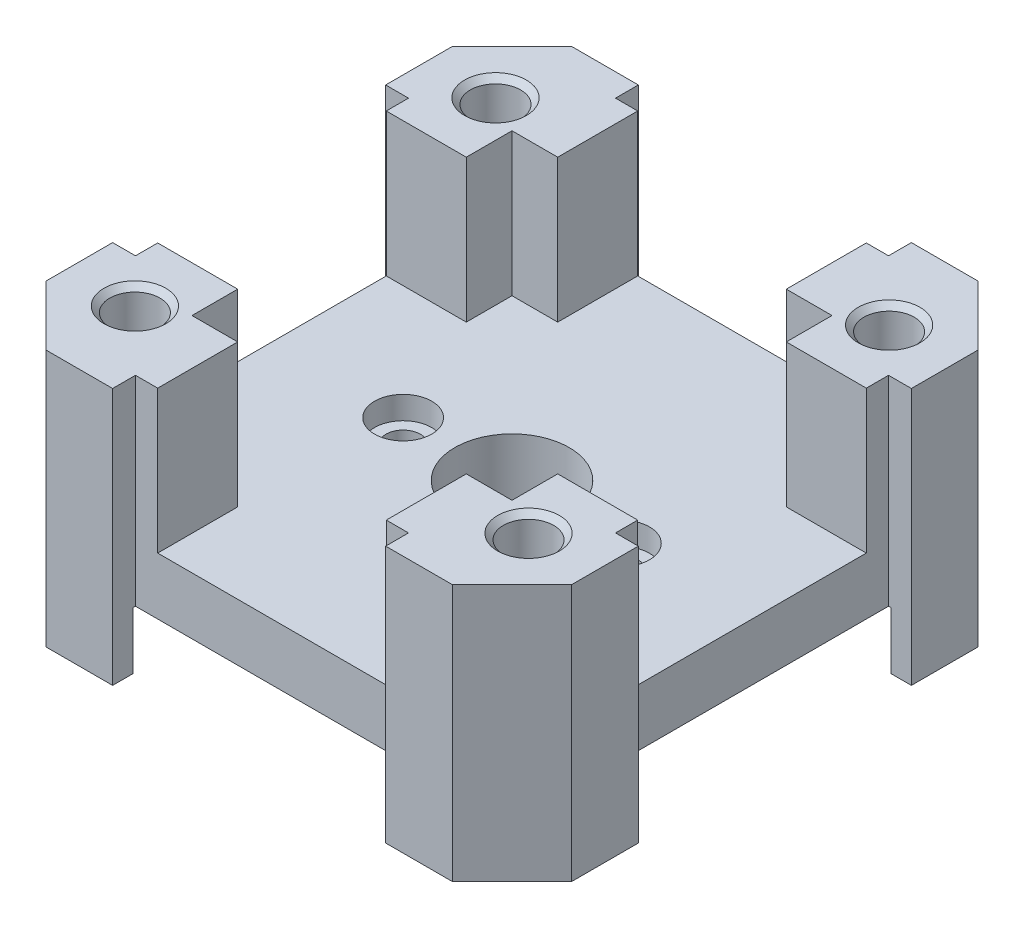
SolidWorks part; units mm, degrees
ref_plane "Front Plane" through (0, 0, 0) normal (0, 0, 1) x (1, 0, 0)
ref_plane "Top Plane" through (0, 0, 0) normal (0, 1, 0) x (1, 0, 0)
ref_plane "Right Plane" through (0, 0, 0) normal (1, 0, 0) x (0, 0, -1)
sketch "Sketch1" plane through (0, 0, 0) normal (0, 1, 0) x (1, 0, 0)
  line L0 (21, 42) -> (21, 0) construction
  line L5 (4.055, 0) -> (37.945, 0)
  line L6 (0, 4.055) -> (0, 37.945)
  line L7 (4.055, 42) -> (37.945, 42)
  line L8 (42, 4.055) -> (42, 37.945)
  line L9 (42, 21) -> (0, 21) construction
  line L10 (0, 37.945) -> (4.055, 42)
  line L11 (37.945, 42) -> (42, 37.945)
  line L12 (37.945, 0) -> (42, 4.055)
  line L13 (4.055, 0) -> (0, 4.055)
  circle A2 centre (11.475, 21) radius 1.5
  circle A3 centre (30.525, 21) radius 1.5
  circle A4 centre (21, 21) radius 5
  point P0 (0, 0)
  point P1 (0, 0)
  point P2 (42, 42)
  point P3 (0, 42)
  point P4 (42, 0)
  dimension "D4" = 3
  dimension "D5" = 3
  dimension "D13" = 10
  dimension "D1" = 42
  dimension "D2" = 42
  dimension "D3" = 19.05
  dimension "D10" = 33.89
  dimension "D9" = 33.89
  dimension "D14" = 16.945
  dimension "D6" = 21
  dimension "D7" = 21
  dimension "D8" = 9.525
  dimension "D11" = 33.89
  dimension "D12" = 33.89
  dimension "D15" = 16.945
  dimension "D16" = 16.945
  dimension "D17" = 16.945
extrude "Boss-Extrude1" add sketch "Sketch1" along normal blind 5
sketch "Sketch2" plane through (0, 5, 0) normal (0, 1, 0) x (1, 0, 0)
  line L45 (35, 7) -> (35, 35)
  line L47 (7, 7) -> (35, 7)
  line L49 (7, 35) -> (7, 7)
  line L51 (35, 35) -> (7, 35)
  line L53 (35, 7) -> (35, 35)
  line L55 (7, 7) -> (35, 7)
  line L57 (7, 35) -> (7, 7)
  line L59 (35, 35) -> (7, 35)
  dimension "D1" = 7
extrude "Boss-Extrude2" add sketch "Sketch2" along normal blind 12.5
sketch "Sketch3" plane through (0, 17.5, 0) normal (0, 1, 0) x (1, 0, 0)
  line L0 (4.055, 42) -> (0, 37.945) construction
  line L1 (0, 4.055) -> (4.055, 0) construction
  line L2 (35, 35) -> (7, 35) construction
  line L3 (7, 7) -> (35, 7) construction
  line L4 (7, 35) -> (7, 7) construction
  line L7 (21, 42) -> (21, 0) construction
  line L8 (37.945, 42) -> (4.055, 42) construction
  line L9 (4.055, 0) -> (37.945, 0) construction
  circle A0 centre (3.7797, 36.775) radius 2.2
  circle A7 centre (3.7797, 5.225) radius 2.2
  circle A8 centre (38.2203, 5.225) radius 2.2
  circle A9 centre (38.2203, 36.775) radius 2.2
  dimension "D1" = 4.4
  dimension "D2" = 3.5
  dimension "D3" = 1.775
  dimension "D4" = 3.2203
  dimension "D5" = 4.4
  dimension "D7" = 1.775
  dimension "D6" = 3.5
extrude "Cut-Extrude1" cut sketch "Sketch3" against normal blind 6
sketch "Sketch4" plane through (0, 0, 0) normal (-1, 0, 0) x (0, 0, 1)
  line L0 (-42, 17.5) -> (-42, 0) construction
  line L1 (-31, 28.0785) -> (-11, 28.0785)
  line L2 (-31, 28.0785) -> (-31, 5)
  line L3 (-31, 5) -> (-11, 5)
  line L4 (-11, 28.0785) -> (-11, 5)
  line L5 (-37.945, 0) -> (-4.055, 0) construction
  dimension "D1" = 20
  dimension "D2" = 11
  dimension "D3" = 5
extrude "Cut-Extrude2" cut sketch "Sketch4" against normal through all both and the other way through all
sketch "Sketch5" plane through (0, 0, -42) normal (0, 0, -1) x (-1, 0, 0)
  line L0 (-42, 17.5) -> (-42, 0) construction
  line L1 (-31, 18.3664) -> (-11, 18.3664)
  line L2 (-31, 18.3664) -> (-31, 5)
  line L3 (-31, 5) -> (-11, 5)
  line L4 (-11, 18.3664) -> (-11, 5)
  line L5 (-37.945, 0) -> (-4.055, 0) construction
  dimension "D1" = 20
  dimension "D2" = 11
  dimension "D3" = 5
extrude "Cut-Extrude3" cut sketch "Sketch5" against normal through all both and the other way through all
sketch "Sketch7" plane through (0, 0, 0) normal (0, -1, 0) x (1, 0, 0)
  line L0 (37.945, 0) -> (32.945, 0)
  line L1 (4.055, 0) -> (0, -4.055)
  line L2 (0, -4.055) -> (0, -9.055)
  line L3 (0, -37.945) -> (4.055, -42)
  line L4 (4.055, -42) -> (9.055, -42)
  line L5 (37.945, -42) -> (42, -37.945)
  line L6 (42, -37.945) -> (42, -32.945)
  line L7 (42, -4.055) -> (37.945, 0)
  line L8 (9.055, 2) -> (9.055, 0)
  line L9 (9.055, -42) -> (9.055, -44)
  line L10 (32.945, -44) -> (32.945, -42)
  line L11 (32.945, 0) -> (32.945, 2)
  line L12 (44, -9.055) -> (42, -9.055)
  line L13 (0, -9.055) -> (-2, -9.055)
  line L14 (-2, -32.945) -> (0, -32.945)
  line L15 (42, -32.945) -> (44, -32.945)
  line L16 (-2, -32.945) -> (-2, -38.7734)
  line L17 (-2, -3.2266) -> (-2, -38.7734) construction
  line L18 (9.055, 2) -> (3.2266, 2)
  line L19 (38.7734, 2) -> (3.2266, 2) construction
  line L20 (9.055, 0) -> (4.055, 0)
  line L21 (37.945, 0) -> (4.055, 0) construction
  line L22 (42, -9.055) -> (42, -4.055)
  line L23 (42, -37.945) -> (42, -4.055) construction
  line L24 (44, -9.055) -> (44, -3.2266)
  line L25 (44, -38.7734) -> (44, -3.2266) construction
  line L26 (32.945, -42) -> (37.945, -42)
  line L27 (4.055, -42) -> (37.945, -42) construction
  line L28 (32.945, -44) -> (38.7734, -44)
  line L29 (3.2266, -44) -> (38.7734, -44) construction
  line L31 (0, -32.945) -> (0, -37.945)
  line L32 (0, -4.055) -> (0, -37.945) construction
  line L44 (44, -3.2266) -> (38.7734, 2)
  line L45 (44, -38.7734) -> (44, -3.2266)
  line L46 (38.7734, -44) -> (44, -38.7734)
  line L47 (3.2266, -44) -> (38.7734, -44)
  line L48 (-2, -38.7734) -> (3.2266, -44)
  line L49 (-2, -3.2266) -> (-2, -38.7734)
  line L50 (3.2266, 2) -> (-2, -3.2266)
  line L51 (38.7734, 2) -> (3.2266, 2)
  line L52 (44, -3.2266) -> (38.7734, 2)
  line L53 (44, -38.7734) -> (44, -32.945)
  line L54 (38.7734, -44) -> (44, -38.7734)
  line L55 (3.2266, -44) -> (9.055, -44)
  line L56 (-2, -38.7734) -> (3.2266, -44)
  line L57 (-2, -3.2266) -> (-2, -9.055)
  line L58 (3.2266, 2) -> (-2, -3.2266)
  line L59 (38.7734, 2) -> (32.945, 2)
  dimension "D3" = 5
  dimension "D4" = 5
  dimension "D5" = 5
  dimension "D6" = 5
  dimension "D7" = 5
  dimension "D1" = 2
  dimension "D2" = 2
extrude "Boss-Extrude3" add sketch "Sketch7" along normal blind 5 and the other way up to surface
sketch "Sketch8" plane through (0, 5, 0) normal (0, 1, 0) x (1, 0, 0)
  circle A0 centre (11.475, 21) radius 2.5
  circle A1 centre (30.525, 21) radius 2.5
  dimension "D1" = 5
  dimension "D2" = 5
extrude "Cut-Extrude4" cut sketch "Sketch8" against normal blind 2
sketch "Sketch9" plane through (0, -5, 0) normal (0, -1, 0) x (1, 0, 0)
  line L0 (-0.2, -9.055) -> (-0.2, -3.9722)
  line L1 (-2, -9.055) -> (0, -9.055) construction
  line L2 (-0.2, -3.9722) -> (3.9722, 0.2)
  line L3 (3.9722, 0.2) -> (38.0278, 0.2)
  line L4 (38.0278, 0.2) -> (42.2, -3.9722)
  line L5 (42.2, -3.9722) -> (42.2, -38.0278)
  line L6 (42.2, -38.0278) -> (38.0278, -42.2)
  line L7 (38.0278, -42.2) -> (3.9722, -42.2)
  line L8 (3.9722, -42.2) -> (-0.2, -38.0278)
  line L9 (-0.2, -38.0278) -> (-0.2, -9.055)
  line L10 (0, -4.055) -> (4.055, 0) construction
  line L11 (4.055, 0) -> (9.055, 0) construction
  line L12 (0, -9.055) -> (0, -4.055) construction
  line L13 (37.945, 0) -> (42, -4.055) construction
  line L14 (42, -9.055) -> (42, -32.945) construction
  line L15 (42, -37.945) -> (37.945, -42) construction
  line L16 (37.945, -42) -> (32.945, -42) construction
  line L17 (4.055, -42) -> (0, -37.945) construction
  dimension "D1" = 0.2
  dimension "D2" = 0.2
  dimension "D3" = 0.2
  dimension "D4" = 0.2
  dimension "D5" = 0.2
  dimension "D6" = 0.2
  dimension "D7" = 0.2
  dimension "D8" = 0.2
extrude "Cut-Extrude5" cut sketch "Sketch9" against normal up to surface (5 mm away) up to face at (30.525, 0, -19.5)
fillet "Fillet1" radius 0.5 8 edges at (38.0278, -2.5, -42.2) (42.2, -2.5, -38.0278) (-0.2, -2.5, -38.0278) (3.9722, -2.5, -42.2) (-0.2, -2.5, -3.9722) (3.9722, -2.5, 0.2) (42.2, -2.5, -3.9722) (38.0278, -2.5, 0.2)
chamfer "Chamfer1" distance 0.5 angle 45 4 edges at (3.7797, 17.5, -3.025) (38.2203, 17.5, -7.425) (38.2203, 17.5, -38.975) (3.7797, 17.5, -34.575)
equation "\"offset\"= 0.20"
equation "\"D2@Sketch9\"=\"offset\""
equation "\"D1@Sketch9\"=\"offset\""
equation "\"D3@Sketch9\"=\"offset\""
equation "\"D8@Sketch9\"=\"offset\""
equation "\"D7@Sketch9\"=\"offset\""
equation "\"D6@Sketch9\"=\"offset\""
equation "\"D5@Sketch9\"=\"offset\""
equation "\"D4@Sketch9\"=\"offset\""
